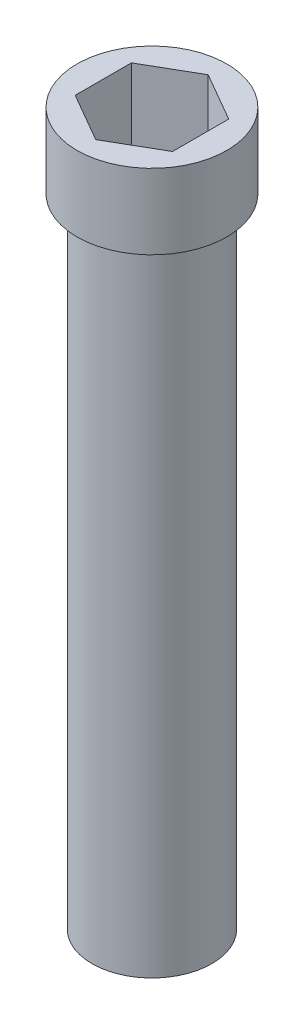
SolidWorks part; units mm, degrees
material "Cast Alloy Steel"
ref_plane "Front Plane" through (0, 0, 0) normal (0, 0, 1) x (1, 0, 0)
ref_plane "Top Plane" through (0, 0, 0) normal (0, 1, 0) x (1, 0, 0)
ref_plane "Right Plane" through (0, 0, 0) normal (1, 0, 0) x (0, 0, -1)
sketch "Sketch1" plane through (0, 0, 0) normal (0, 1, 0) x (1, 0, 0)
  circle A0 centre (0, 0) radius 1.6
  dimension "D1" = 3.2
extrude "Length" add sketch "Sketch1" along normal blind 17
sketch "Sketch2" plane through (0, 17, 0) normal (0, 1, 0) x (1, 0, 0)
  circle A0 centre (0, 0) radius 2
  dimension "D1" = 4
extrude "Cap" add sketch "Sketch2" along normal blind 2
sketch "Sketch3" plane through (0, 19, 0) normal (0, 1, 0) x (1, 0, 0)
  line L1 (0, 1.5) -> (-1.299, 0.75)
  line L2 (-1.299, 0.75) -> (-1.299, -0.75)
  line L3 (-1.299, -0.75) -> (0, -1.5)
  line L4 (0, -1.5) -> (1.299, -0.75)
  line L5 (1.299, -0.75) -> (1.299, 0.75)
  line L6 (1.299, 0.75) -> (0, 1.5)
  circle A0 centre (0, 0) radius 1.299 construction
  dimension "D1" = 1.5
extrude "Hex" cut sketch "Sketch3" against normal blind 2
